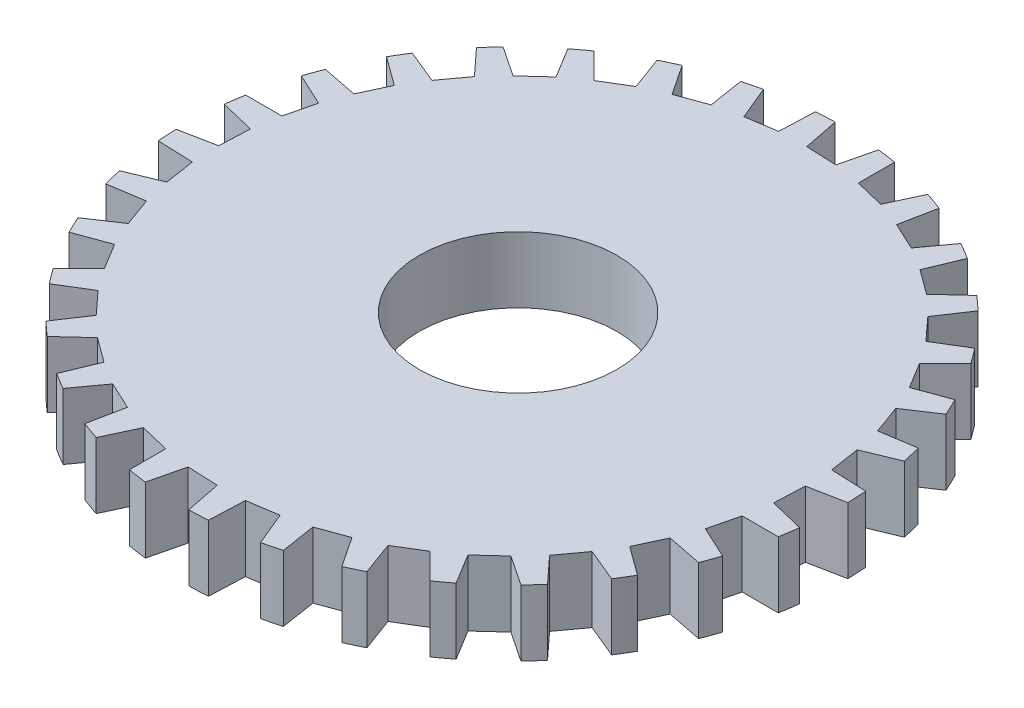
SolidWorks part; units mm, degrees
ref_plane "Alzado" through (0, 0, 0) normal (0, 0, 1) x (1, 0, 0)
ref_plane "Planta" through (0, 0, 0) normal (0, 1, 0) x (1, 0, 0)
ref_plane "Vista lateral" through (0, 0, 0) normal (1, 0, 0) x (0, 0, -1)
sketch "Croquis1" plane through (0, 0, 0) normal (0, 1, 0) x (1, 0, 0)
  circle A0 centre (0, 0) radius 50
  dimension "D1" = 100
extrude "Saliente-Extruir1" add sketch "Croquis1" along normal blind 10
sketch "Croquis2" plane through (0, 10, 0) normal (0, 1, 0) x (1, 0, 0)
  circle A0 centre (0, 0.9266) radius 15
  dimension "D1" = 30
extrude "Cortar-Extruir1" cut sketch "Croquis2" against normal blind 10
sketch "Croquis3" plane through (0, 10, 0) normal (0, 1, 0) x (1, 0, 0)
  line L12 (4.7239, 44.4066) -> (0.1137, 44.6069)
  line L16 (0.1137, 44.6069) -> (-0.9544, 49.9909)
  line L17 (4.7239, 44.4066) -> (5.9899, 49.6399)
  circle A0 centre (0, 0) radius 50 construction
  arc A2 (-0.9544, 49.9909) -> (5.9899, 49.6399) centre (0, 0) cw
extrude "Cortar-Extruir14" cut sketch "Croquis3" against normal blind 14 contours L16 A2 L17 L12
pattern_circular "MatrizC1" count 32 over 360 about axis through (0, 0, 0) along (0, 1, 0) of "Cortar-Extruir14"
